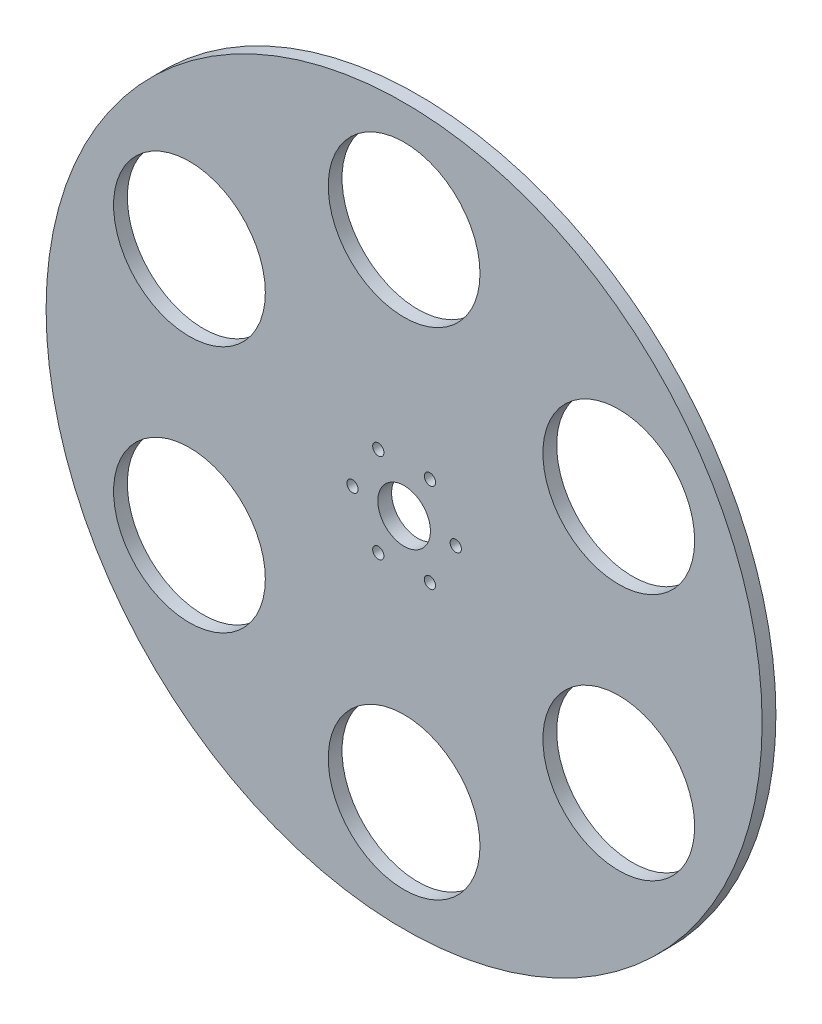
SolidWorks part; units mm, degrees
material "6061 Alloy"
ref_plane "Front Plane" through (0, 0, 0) normal (0, 0, 1) x (1, 0, 0)
ref_plane "Top Plane" through (0, 0, 0) normal (0, 1, 0) x (1, 0, 0)
ref_plane "Right Plane" through (0, 0, 0) normal (1, 0, 0) x (0, 0, -1)
sketch "Sketch1" plane through (0, 0, 0) normal (0, 0, 1) x (1, 0, 0)
  line L0 (6.5991, -21.59) -> (27.0559, -57.0222) construction
  line L1 (20.4568, -68.4522) -> (-20.4568, -68.4522) construction
  line L2 (-27.0559, -57.0222) -> (-6.5991, -21.59) construction
  line L3 (-15.3979, -16.51) -> (-35.8547, -51.9422) construction
  line L4 (-49.0529, -51.9422) -> (-69.5097, -16.51) construction
  line L5 (-62.9106, -5.08) -> (-21.997, -5.08) construction
  line L6 (-21.997, 5.08) -> (-62.9106, 5.08) construction
  line L7 (-69.5097, 16.51) -> (-49.0529, 51.9422) construction
  line L8 (-35.8547, 51.9422) -> (-15.3979, 16.51) construction
  line L9 (-6.5991, 21.59) -> (-27.0559, 57.0222) construction
  line L10 (-20.4568, 68.4522) -> (20.4568, 68.4522) construction
  line L11 (27.0559, 57.0222) -> (6.5991, 21.59) construction
  line L12 (15.3979, 16.51) -> (35.8547, 51.9422) construction
  line L13 (49.0529, 51.9422) -> (69.5097, 16.51) construction
  line L14 (62.9106, 5.08) -> (21.997, 5.08) construction
  line L15 (21.997, -5.08) -> (62.9106, -5.08) construction
  line L16 (69.5097, -16.51) -> (49.0529, -51.9422) construction
  line L17 (35.8547, -51.9422) -> (15.3979, -16.51) construction
  circle A0 centre (0, 114.3) radius 34.9885
  circle A1 centre (98.9867, 57.15) radius 34.9885
  circle A2 centre (98.9867, -57.15) radius 34.9885
  circle A3 centre (0, -114.3) radius 34.9885
  circle A4 centre (-98.9867, -57.15) radius 34.9885
  circle A5 centre (-98.9867, 57.15) radius 34.9885
  circle A6 centre (0, 0) radius 165.1
  circle A7 centre (0, 0) radius 12.1285
  arc A8 (-20.4568, -68.4522) -> (-27.0559, -57.0222) centre (-20.4568, -60.8322) cw construction
  arc A9 (27.0559, -57.0222) -> (20.4568, -68.4522) centre (20.4568, -60.8322) cw construction
  arc A10 (6.5991, -21.59) -> (-6.5991, -21.59) centre (0, -25.4) ccw construction
  arc A11 (-69.5097, -16.51) -> (-62.9106, -5.08) centre (-62.9106, -12.7) cw construction
  arc A12 (-35.8547, -51.9422) -> (-49.0529, -51.9422) centre (-42.4538, -48.1322) cw construction
  arc A13 (-15.3979, -16.51) -> (-21.997, -5.08) centre (-21.997, -12.7) ccw construction
  arc A14 (-49.0529, 51.9422) -> (-35.8547, 51.9422) centre (-42.4538, 48.1322) cw construction
  arc A15 (-62.9106, 5.08) -> (-69.5097, 16.51) centre (-62.9106, 12.7) cw construction
  arc A16 (-21.997, 5.08) -> (-15.3979, 16.51) centre (-21.997, 12.7) ccw construction
  arc A17 (20.4568, 68.4522) -> (27.0559, 57.0222) centre (20.4568, 60.8322) cw construction
  arc A18 (-27.0559, 57.0222) -> (-20.4568, 68.4522) centre (-20.4568, 60.8322) cw construction
  arc A19 (-6.5991, 21.59) -> (6.5991, 21.59) centre (0, 25.4) ccw construction
  arc A20 (69.5097, 16.51) -> (62.9106, 5.08) centre (62.9106, 12.7) cw construction
  arc A21 (35.8547, 51.9422) -> (49.0529, 51.9422) centre (42.4538, 48.1322) cw construction
  arc A22 (15.3979, 16.51) -> (21.997, 5.08) centre (21.997, 12.7) ccw construction
  arc A23 (49.0529, -51.9422) -> (35.8547, -51.9422) centre (42.4538, -48.1322) cw construction
  arc A24 (62.9106, -5.08) -> (69.5097, -16.51) centre (62.9106, -12.7) cw construction
  arc A25 (21.997, -5.08) -> (15.3979, -16.51) centre (21.997, -12.7) ccw construction
  point P16 (0, 0)
  point P22 (-33.655, -68.4522)
  point P27 (0, -10.16)
  point P76 (0, 0)
  dimension "D1" = 69.977
  dimension "D4" = 330.2
  dimension "D5" = 24.257
  dimension "D6" = 67.31
  dimension "D7" = 7.62
  dimension "D10" = 114.3
  dimension "D2" = 114.3
  dimension "D8" = 25.4
  dimension "D3" = 6
  dimension "D9" = 6
extrude "Boss-Extrude1" add sketch "Sketch1" along normal mid plane 6.35
sketch "Sketch2" plane through (0, 0, -3.175) normal (0, 0, -1) x (-1, 0, 0)
  circle A0 centre (-23.8125, 0) radius 2.5908
  circle A2 centre (-11.9062, 20.6222) radius 2.5908
  circle A3 centre (11.9063, 20.6222) radius 2.5908
  circle A4 centre (23.8125, 0) radius 2.5908
  circle A5 centre (11.9062, -20.6222) radius 2.5908
  circle A6 centre (-11.9063, -20.6222) radius 2.5908
  circle A8 centre (0, 0) radius 12.1285 construction
  point P16 (0, 0)
  dimension "D1" = 5.1816
  dimension "D2" = 47.625
  dimension "D4" = 23.8125
  dimension "D3" = 6
extrude "Cut-Extrude1" cut sketch "Sketch2" against normal up to surface (6.35 mm away) up to face at (-63.9982, -57.15, 3.175)
